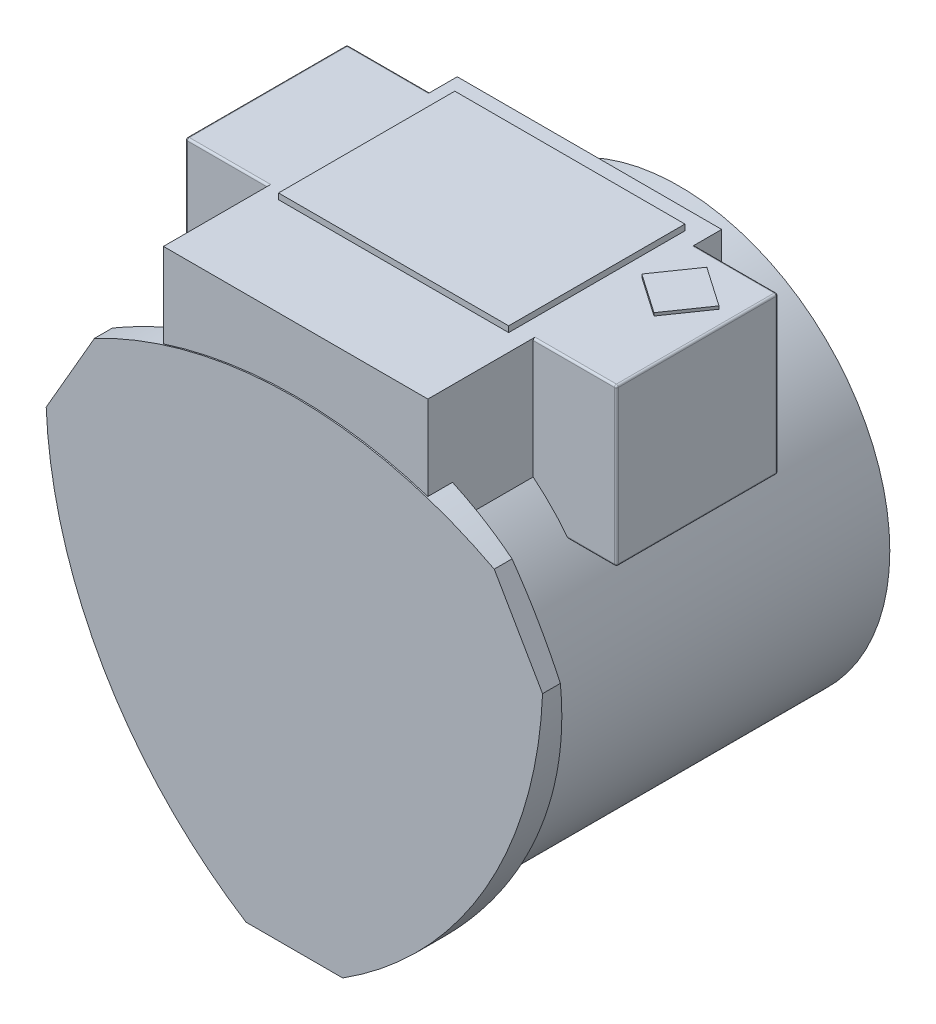
SolidWorks part; units mm, degrees
ref_plane "前视基准面" through (0, 0, 0) normal (0, 0, 1) x (1, 0, 0)
ref_plane "上视基准面" through (0, 0, 0) normal (0, 1, 0) x (1, 0, 0)
ref_plane "右视基准面" through (0, 0, 0) normal (1, 0, 0) x (0, 0, -1)
sketch "草图1" plane through (0, 0, 0) normal (0, 0, 1) x (1, 0, 0)
  circle A0 centre (0, 0) radius 215
  dimension "D1" = 430
extrude "凸台-拉伸1" add sketch "草图1" along normal blind 363
sketch "草图4" plane through (0, 0, 0) normal (0, 1, 0) x (1, 0, 0)
  line L0 (314.6296, -393) -> (0, -393)
  line L1 (0, 172.6389) -> (0, -955.7224) construction
  line L2 (-215, -363) -> (215, -363) construction
  line L3 (0, -327.9077) -> (0, -393)
  arc A0 (314.6296, -393) -> (0, -327.9077) centre (0, -1120.8493) ccw
  dimension "D1" = 30
revolve "旋转1" add sketch "草图4" angle 360 about L1
sketch "草图5" plane through (0, 0, 393) normal (0, 0, 1) x (1, 0, 0)
  line L0 (0, -215) -> (0, 0)
  line L1 (-186.1955, 107.5) -> (0, 0)
  line L2 (186.1955, 107.5) -> (0, 0)
  line L3 (186.1955, 107.5) -> (252.1535, 145.5809) construction
  line L4 (204.0832, 174.8077) -> (253.4295, 89.3374)
  line L5 (49.3463, -264.1451) -> (-49.3463, -264.1451)
  line L6 (-253.4295, 89.3374) -> (-204.0832, 174.8077)
  circle A0 centre (0, 0) radius 215 construction
  circle A1 centre (0, 0) radius 215
  arc A2 (-243.802, 106.0128) -> (-30.0912, -264.1451) centre (186.1955, 107.5) ccw
  arc A3 (30.0912, -264.1451) -> (243.802, 106.0128) centre (-186.1955, 107.5) ccw
  arc A4 (213.7107, 158.1323) -> (-213.7107, 158.1323) centre (0, -215) ccw
  arc A5 (-253.4295, 89.3374) -> (-49.3463, -264.1451) centre (186.1955, 107.5) ccw
  arc A6 (49.3463, -264.1451) -> (253.4295, 89.3374) centre (-186.1955, 107.5) ccw
  arc A7 (204.0832, 174.8077) -> (-204.0832, 174.8077) centre (0, -215) ccw
  arc A9 (252.1535, 145.5809) -> (-252.1535, 145.5809) centre (0, -215) ccw construction
  arc A10 (0, -291.1618) -> (252.1535, 145.5809) centre (-186.1955, 107.5) ccw construction
  arc A11 (242.5709, 140.0484) -> (-242.5709, 140.0484) centre (0, -215) ccw construction
  arc A12 (0, -280.0968) -> (242.5709, 140.0484) centre (-186.1955, 107.5) ccw construction
  arc A13 (-242.5709, 140.0484) -> (0, -280.0968) centre (186.1955, 107.5) ccw construction
  arc A14 (-252.1535, 145.5809) -> (0, -291.1618) centre (186.1955, 107.5) ccw construction
  point P9 (0, 0)
  point P19 (228.7563, 132.0725)
  point P27 (0, 0)
  dimension "D2" = 10
  dimension "D1" = 3
  dimension "D3" = 3
extrude "切除-拉伸-薄壁1" cut sketch "草图5" against normal blind 107 thin contours L6 A7 L4 A6 L5 A5
sketch3d "3D草图12"
  line L0 (0, 290, 0) -> (0, 290, 443.0924) construction
  line L1 (-135, 290, 201.6912) -> (135, 290, 201.6912) construction
  line L2 (-135, 290, 91.6912) -> (135, 290, 91.6912)
  line L3 (-135, 290, 91.6912) -> (-135, 290, 119.1912)
  line L4 (-135, 290, 391.6912) -> (135, 290, 391.6912)
  line L5 (135, 290, 91.6912) -> (135, 290, 119.1912)
  line L6 (0, 290, 391.6912) -> (0, 290, 91.6912) construction
  line L7 (-135, 290, 241.6912) -> (135, 290, 241.6912) construction
  line L8 (-135, 290, 284.1912) -> (-135, 290, 391.6912)
  line L9 (-220, 290, 119.1912) -> (-220, 290, 284.1912)
  line L10 (-220, 290, 119.1912) -> (-135, 290, 119.1912)
  line L11 (135, 290, 284.1912) -> (135, 290, 391.6912)
  line L12 (-220, 290, 284.1912) -> (-135, 290, 284.1912)
  line L13 (-50, 290, 201.6912) -> (-220, 290, 201.6912) construction
  line L14 (-135, 290, 119.1912) -> (-135, 290, 241.6912) construction
  line L16 (135, 290, 119.1912) -> (220, 290, 119.1912)
  line L17 (220, 290, 119.1912) -> (220, 290, 284.1912)
  line L18 (135, 290, 284.1912) -> (220, 290, 284.1912)
  line L19 (220, 290, 201.6912) -> (50, 290, 201.6912) construction
  line L20 (135, 290, 119.1912) -> (135, 290, 284.1912) construction
  point P3 (0, 290, 241.6912)
  dimension "D2" = 270
  dimension "D1" = 300
  dimension "D3" = 190
  dimension "D4" = 165
  dimension "D5" = 85
  dimension "D6" = 165
  dimension "D7" = 85
extrude "凸台-拉伸4" add sketch "3D草图12" along direction (0, 1, 0) on the side of the normal blind 160
sketch "草图10" plane through (0, 290, 0) normal (0, 1, 0) x (1, 0, 0)
  line L0 (0, -391.6912) -> (0, -26.2076) construction
  line L1 (0, -26.2076) -> (0, 0) construction
  line L2 (-220, -201.6912) -> (220, -201.6912) construction
  line L4 (-117.5, -291.6912) -> (117.5, -291.6912)
  line L5 (-117.5, -291.6912) -> (-117.5, -111.6912)
  line L6 (-117.5, -111.6912) -> (117.5, -111.6912)
  line L7 (117.5, -291.6912) -> (117.5, -111.6912)
  line L8 (0, -111.6912) -> (0, -291.6912) construction
  line L9 (-117.5, -201.6912) -> (117.5, -201.6912) construction
  line L12 (135, -284.1912) -> (220, -284.1912)
  line L13 (220, -284.1912) -> (220, -119.1912)
  line L14 (220, -119.1912) -> (135, -119.1912)
  line L15 (135, -119.1912) -> (135, -91.6912)
  line L16 (135, -91.6912) -> (-135, -91.6912)
  line L17 (-135, -91.6912) -> (-135, -119.1912)
  line L18 (-135, -119.1912) -> (-220, -119.1912)
  line L19 (-220, -119.1912) -> (-220, -284.1912)
  line L20 (-220, -284.1912) -> (-135, -284.1912)
  line L21 (-135, -284.1912) -> (-135, -391.6912)
  line L22 (-135, -391.6912) -> (135, -391.6912)
  line L23 (135, -391.6912) -> (135, -284.1912)
  line L24 (135, -284.1912) -> (220, -284.1912)
  line L25 (220, -284.1912) -> (220, -119.1912)
  line L26 (220, -119.1912) -> (135, -119.1912)
  line L27 (135, -119.1912) -> (135, -91.6912)
  line L28 (135, -91.6912) -> (-135, -91.6912)
  line L29 (-135, -91.6912) -> (-135, -119.1912)
  line L30 (-135, -119.1912) -> (-220, -119.1912)
  line L31 (-220, -119.1912) -> (-220, -284.1912)
  line L32 (-220, -284.1912) -> (-135, -284.1912)
  line L33 (-135, -284.1912) -> (-135, -391.6912)
  line L34 (-135, -391.6912) -> (135, -391.6912)
  line L35 (135, -391.6912) -> (135, -284.1912)
  point P18 (0, -201.6912)
  dimension "D2" = 235
  dimension "D3" = 100
  dimension "D1" = 0
extrude "凸台-拉伸5" add sketch "草图10" along normal blind 6 contours L4 L7 L6 L5
fillet "圆角3" radius 2 16 edges
ref_plane "基准面1" through (-80, 0, 0) normal (-1, 0, 0) x (0, 0, 1)
ref_plane "基准面2" through (-180, 0, 0) normal (1, 0, 0) x (0, 0, -1)
sketch "草图33" plane through (0, 290, 0) normal (0, 1, 0) x (1, 0, 0)
  line L0 (163.8186, -135.7013) -> (204.2072, -163.6627)
  line L1 (163.8186, -135.7013) -> (136.6837, -174.8962)
  line L2 (204.2072, -163.6627) -> (177.0723, -202.8575)
  line L3 (136.6837, -174.8962) -> (177.0723, -202.8575)
extrude "凸台-拉伸20" add sketch "草图33" along normal blind 3
ref_plane "基准面3" through (-23.9985, 0, 34.6644) normal (0.5692, 0, -0.8222) x (-0.8222, 0, -0.5692)
ref_plane "基准面4" through (0, 0, 0) normal (0, 0, -1) x (-1, 0, 0)
sketch "草图34" plane through (0, 0, 0) normal (0, 0, -1) x (-1, 0, 0)
  circle A0 centre (0, 0) radius 50
extrude "凸台-拉伸21" add sketch "草图34" along normal blind 10
